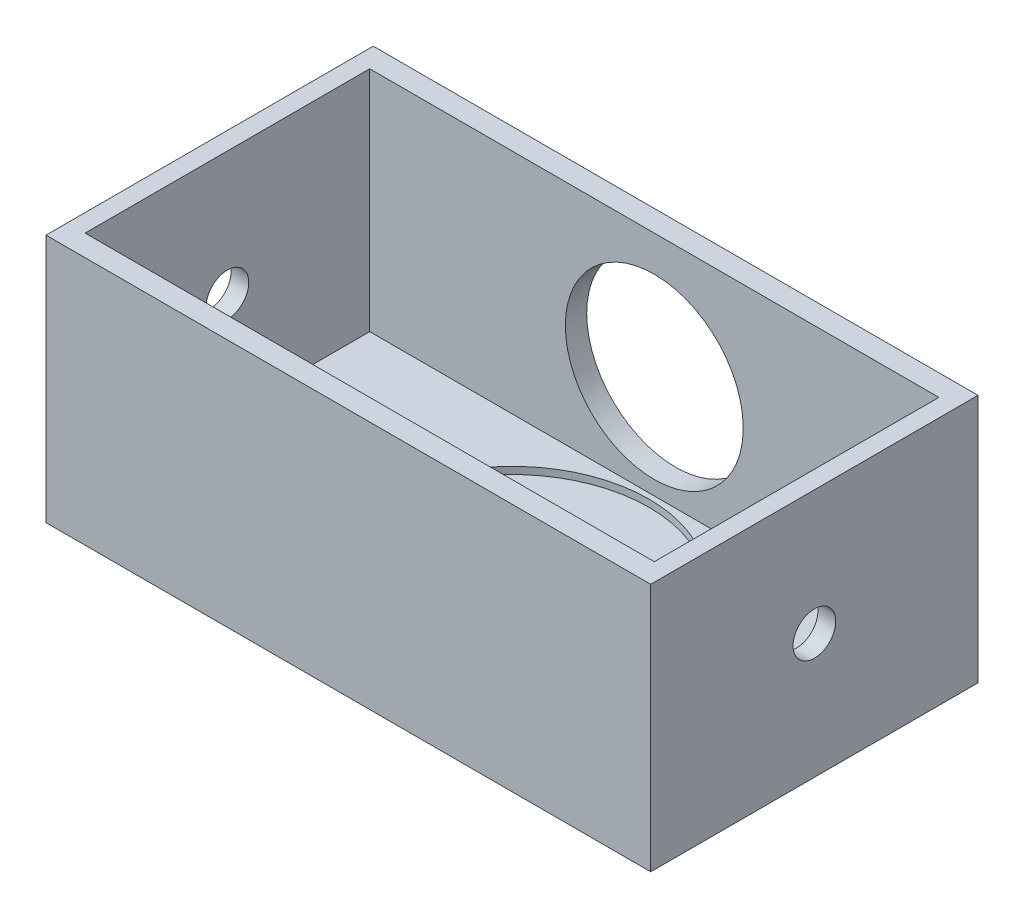
SolidWorks part; units mm, degrees
ref_plane "Front Plane" through (0, 0, 0) normal (0, 0, 1) x (1, 0, 0)
ref_plane "Top Plane" through (0, 0, 0) normal (0, 1, 0) x (1, 0, 0)
ref_plane "Right Plane" through (0, 0, 0) normal (1, 0, 0) x (0, 0, -1)
sketch "Sketch1" plane through (0, 0, 0) normal (0, 1, 0) x (1, 0, 0)
  line L1 (-42.5, -23) -> (42.5, -23)
  line L2 (-42.5, -23) -> (-42.5, 23)
  line L3 (-42.5, 23) -> (42.5, 23)
  line L4 (42.5, -23) -> (42.5, 23)
  line L5 (-42.5, -23) -> (42.5, 23) construction
  line L6 (-42.5, 23) -> (42.5, -23) construction
  point P0 (0, 0)
  dimension "D1" = 85
  dimension "D2" = 46
extrude "Boss-Extrude1" add sketch "Sketch1" along normal blind 35
sketch "Sketch2" plane through (0, 35, 0) normal (0, 1, 0) x (1, 0, 0)
  line L1 (-40, -20) -> (40, -20)
  line L2 (-40, -20) -> (-40, 20)
  line L3 (-40, 20) -> (40, 20)
  line L4 (40, -20) -> (40, 20)
  line L5 (-40, -20) -> (40, 20) construction
  line L6 (-40, 20) -> (40, -20) construction
  point P0 (0, 0)
  dimension "D1" = 80
  dimension "D2" = 40
sketch "Sketch3" plane through (0, 0, -23) normal (0, 0, -1) x (-1, 0, 0)
  line L0 (0, 21.1557) -> (0, -16.6176) construction
  line L1 (-42.5, 17.5) -> (42.5, 17.5) construction
  line L2 (-42.5, 35) -> (-42.5, 0) construction
  line L3 (42.5, 35) -> (42.5, 0) construction
  circle A0 centre (0, 17.5) radius 12.5
  dimension "D1" = 25
extrude "Cut-Extrude2" cut sketch "Sketch3" against normal blind 10
sketch "Sketch4" plane through (42.5, 0, 0) normal (1, 0, 0) x (0, 0, -1)
  line L0 (-23, 17.5) -> (23, 17.5) construction
  line L1 (-23, 35) -> (-23, 0) construction
  line L2 (23, 35) -> (23, 0) construction
  line L3 (0, 0) -> (0, 35) construction
  line L4 (-23, 35) -> (23, 35) construction
  circle A0 centre (0, 17.5) radius 3
  dimension "D1" = 6
extrude "Cut-Extrude3" cut sketch "Sketch4" against normal through all
extrude "Cut-Extrude4" cut sketch "Sketch2" against normal through all
sketch "Sketch5" plane through (0, 0, 0) normal (0, 1, 0) x (1, 0, 0)
  line L6 (-40, -20) -> (40, -20)
  line L7 (-40, -20) -> (-40, 20)
  line L8 (-40, 20) -> (40, 20)
  line L9 (40, -20) -> (40, 20)
  line L10 (-40, -20) -> (40, 20) construction
  line L11 (-40, 20) -> (40, -20) construction
  point P0 (0, 0)
  point P2 (0, 0)
extrude "Boss-Extrude2" add sketch "Sketch5" along normal blind 3
sketch "Sketch6" plane through (0, 3, 0) normal (0, 1, 0) x (1, 0, 0)
  circle A0 centre (0, 0) radius 1.875
  circle A1 centre (0, 0) radius 19.25
  dimension "D1" = 3.75
  dimension "D2" = 38.5
extrude "Cut-Extrude6" cut sketch "Sketch6" against normal blind 1
sketch "Sketch7" plane through (0, 3, 0) normal (0, 1, 0) x (1, 0, 0)
  circle A0 centre (0, 0) radius 1.875
extrude "Boss-Extrude3" add sketch "Sketch7" along normal blind 5
